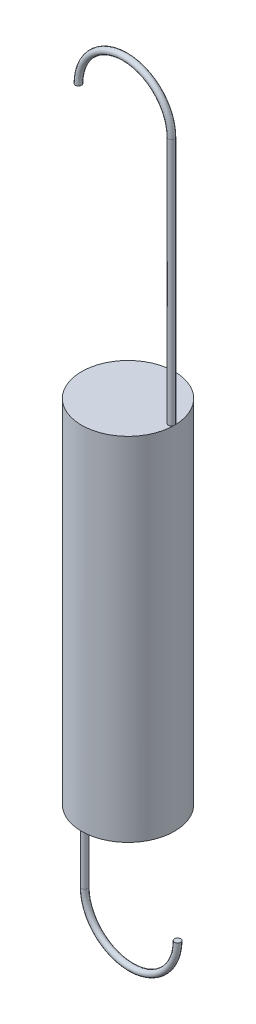
SolidWorks part; units mm, degrees
ref_plane "Front Plane" through (0, 0, 0) normal (0, 0, 1) x (1, 0, 0)
ref_plane "Top Plane" through (0, 0, 0) normal (0, 1, 0) x (1, 0, 0)
ref_plane "Right Plane" through (0, 0, 0) normal (1, 0, 0) x (0, 0, -1)
sketch "Sketch1" plane through (0, 0, 0) normal (0, 1, 0) x (1, 0, 0)
  circle A0 centre (0, 0) radius 3
  dimension "D1" = 6
extrude "Boss-Extrude1" add sketch "Sketch1" along normal blind 22.7
sketch "Sketch2" plane through (0, 0, 0) normal (0, 0, 1) x (1, 0, 0)
  line L0 (2.8, 22.7) -> (2.8, 38.7)
  line L2 (3, 22.7) -> (-3, 22.7) construction
  line L3 (3, 0) -> (3, 22.7) construction
  arc A0 (2.8, 38.7) -> (-3.2, 38.7) centre (-0.2, 38.7) ccw
  point P5 (-4.5774, 31.4113)
  point P6 (0, 0)
  point P9 (0, 0)
  point P10 (0, 0)
  point P13 (2.8, 13.1974)
  point P14 (2.8, 22.7)
  dimension "D1" = 16
  dimension "D2" = 3
  dimension "D3" = 0.2
sketch "Sketch3" plane through (0, 22.7, 0) normal (0, 1, 0) x (1, 0, 0)
  line L0 (-3.2, 0) -> (2.8, 0) construction
  circle A0 centre (2.8, 0) radius 0.2
  dimension "D1" = 0.4
sweep "Sweep1" add profiles "Sketch3" path "Sketch2"
sketch "Sketch4" plane through (0, 0, 0) normal (0, 0, 1) x (1, 0, 0)
  line L0 (-2.8, 0) -> (-2.8, -6)
  line L1 (-3, 0) -> (3, 0) construction
  line L3 (-3, 22.7) -> (-3, 0) construction
  arc A0 (-2.8, -6) -> (3.2, -6) centre (0.2, -6) ccw
  point P6 (0, 0)
  dimension "D1" = 3
  dimension "D2" = 6
  dimension "D3" = 0.2
sketch "Sketch5" plane through (0, 0, 0) normal (0, -1, 0) x (1, 0, 0)
  circle A0 centre (-2.8, 0) radius 0.2
  dimension "D1" = 0.4
sweep "Sweep2" add profiles "Sketch5" path "Sketch4"
